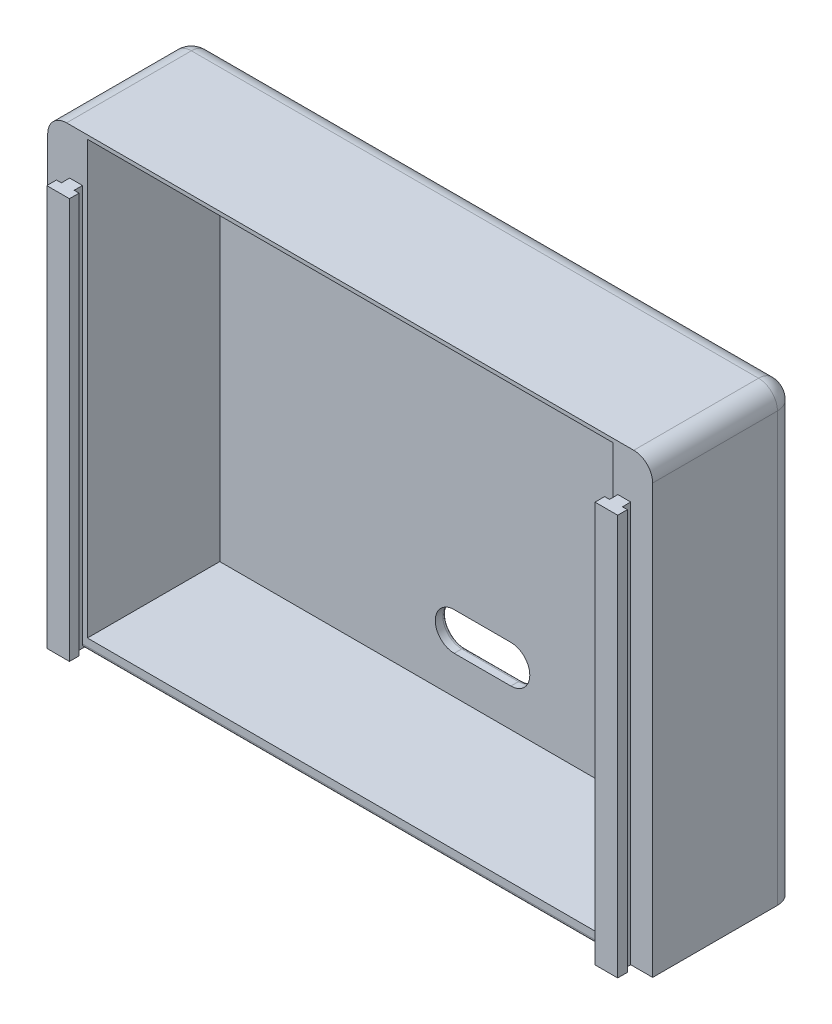
SolidWorks part; units mm, degrees
ref_plane "Front Plane" through (0, 0, 0) normal (0, 0, 1) x (1, 0, 0)
ref_plane "Top Plane" through (0, 0, 0) normal (0, 1, 0) x (1, 0, 0)
ref_plane "Right Plane" through (0, 0, 0) normal (1, 0, 0) x (0, 0, -1)
sketch "Sketch1" plane through (0, 0, 0) normal (0, 0, 1) x (1, 0, 0)
  line L1 (-80, -59.125) -> (80, -59.125)
  line L2 (-80, -59.125) -> (-80, 59.125)
  line L3 (-80, 59.125) -> (80, 59.125)
  line L4 (80, -59.125) -> (80, 59.125)
  line L5 (-80, -59.125) -> (80, 59.125) construction
  line L6 (-80, 59.125) -> (80, -59.125) construction
  point P0 (0, 0)
  dimension "D1" = 118.25
  dimension "D2" = 160
extrude "Main Body" add sketch "Sketch1" along normal blind 38
sketch "Sketch2" plane through (0, -59.125, 0) normal (0, -1, 0) x (1, 0, 0)
  line L0 (-80, 38) -> (-65, 38) construction
  line L1 (-80, 38) -> (80, 38) construction
  line L2 (-72.5, 38) -> (-74.2, 38)
  line L3 (-74.2, 38) -> (-74.2, 40.2)
  line L4 (-74.2, 40.2) -> (-75.5, 40.2)
  line L5 (-75.5, 40.2) -> (-75.5, 42.75)
  line L6 (-75.5, 42.75) -> (-69.5, 42.75)
  line L7 (-69.5, 42.75) -> (-69.5, 40.2)
  line L8 (-69.5, 40.2) -> (-70.8, 40.2)
  line L9 (-70.8, 40.2) -> (-70.8, 38)
  line L10 (-70.8, 38) -> (-72.5, 38)
  dimension "D1" = 15
  dimension "D2" = 1.7
  dimension "D3" = 2.2
  dimension "D4" = 1.3
  dimension "D5" = 2.55
  dimension "D6" = 6
  dimension "D7" = 2.55
  dimension "D8" = 1.3
  dimension "D9" = 2.2
extrude "Track" add sketch "Sketch2" against normal blind 106
mirror "Mirror Track" about plane through (0, 0, 0) normal (1, 0, 0) of "Track"
fillet "Fillet" radius 5 5 edges at (80, 0, 0) (80, 59.125, 19) (0, 59.125, 0) (-80, 0, 0) (-80, 59.125, 19)
sketch "Sketch3" plane through (0, 0, 38) normal (0, 0, 1) x (1, 0, 0)
  line L1 (-69.5, -56.125) -> (69.5, -56.125)
  line L2 (-69.5, -56.125) -> (-69.5, 56.125)
  line L3 (-69.5, 56.125) -> (69.5, 56.125)
  line L4 (69.5, -56.125) -> (69.5, 56.125)
  line L5 (-69.5, -56.125) -> (69.5, 56.125) construction
  line L6 (-69.5, 56.125) -> (69.5, -56.125) construction
  point P0 (0, 0)
  dimension "D1" = 112.25
  dimension "D2" = 139
extrude "Storage" cut sketch "Sketch3" against normal blind 35
sketch "Sketch4" plane through (0, 0, 3) normal (0, 0, 1) x (1, 0, 0)
  line L0 (0, -56.125) -> (0, -41.125) construction
  line L1 (-69.5, -56.125) -> (69.5, -56.125) construction
  line L2 (-7.5, -41.125) -> (7.5, -41.125) construction
  line L4 (-7.5, -36.125) -> (7.5, -36.125)
  line L5 (-7.5, -46.125) -> (7.5, -46.125)
  arc A0 (-7.5, -36.125) -> (-7.5, -46.125) centre (-7.5, -41.125) ccw
  arc A1 (7.5, -46.125) -> (7.5, -36.125) centre (7.5, -41.125) ccw
  point P9 (0, -41.125)
  dimension "D1" = 15
extrude "Wire Hole" cut sketch "Sketch4" against normal blind 25
fillet "Fillet2" radius 1 5 edges at (0, -46.125, 0) (0, -36.125, 0) (-12.5, -41.125, 0) (0, -59.125, 38) (12.5, -41.125, 0)
chamfer "Chamfer1" distance 2 angle 45 1 edges at (0, 56.125, 38)
